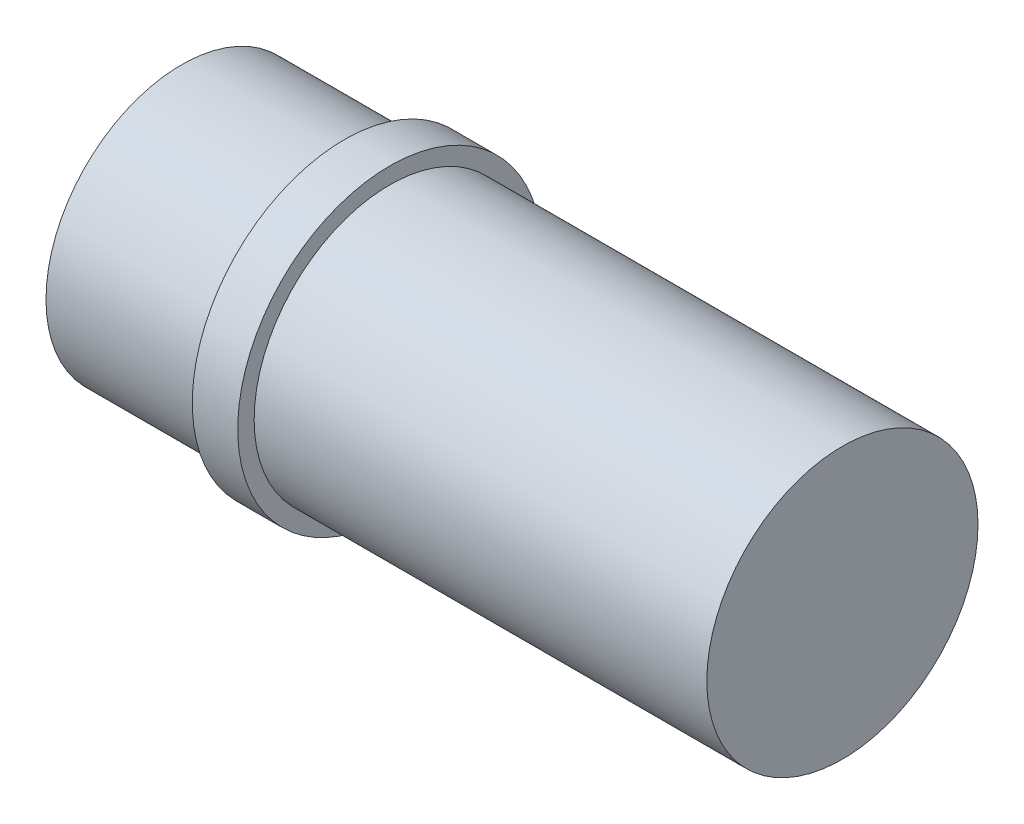
SolidWorks part; units mm, degrees
ref_plane "Front Plane" through (0, 0, 0) normal (0, 0, 1) x (1, 0, 0)
ref_plane "Top Plane" through (0, 0, 0) normal (0, 1, 0) x (1, 0, 0)
ref_plane "Right Plane" through (0, 0, 0) normal (1, 0, 0) x (0, 0, -1)
sketch "Sketch1" plane through (0, 0, 0) normal (1, 0, 0) x (0, 0, -1)
  circle A0 centre (0, 0) radius 12.5
  dimension "D1" = 25
extrude "Boss-Extrude1" add sketch "Sketch1" along normal blind 15
sketch "Sketch2" plane through (15, 0, 0) normal (1, 0, 0) x (0, 0, -1)
  circle A0 centre (0, 0) radius 15
  dimension "D1" = 30
scale "Scale1" scale about centroid uniform scaling yes scale factor 1.9329
scale "Scale2" scale about centroid uniform scaling yes scale factor 1.5
sketch "Sketch3" plane through (29.2451, 0, 0) normal (1, 0, 0) x (0, 0, -1)
  circle A0 centre (0, 0) radius 40.6334
extrude "Boss-Extrude2" add sketch "Sketch3" along normal blind 12.15
sketch "Sketch4" plane through (41.3951, 0, 0) normal (1, 0, 0) x (0, 0, -1)
  circle A0 centre (0, 0) radius 36.2419 construction
  circle A1 centre (0, 0) radius 36.2419
extrude "Boss-Extrude3" add sketch "Sketch4" along normal blind 50
sketch "Sketch5" plane through (91.3951, 0, 0) normal (1, 0, 0) x (0, 0, -1)
  circle A1 centre (0, 0) radius 36.2419
  circle A2 centre (0, 0) radius 36.2419
  dimension "D1" = 0
extrude "Boss-Extrude4" add sketch "Sketch5" along normal blind 71
